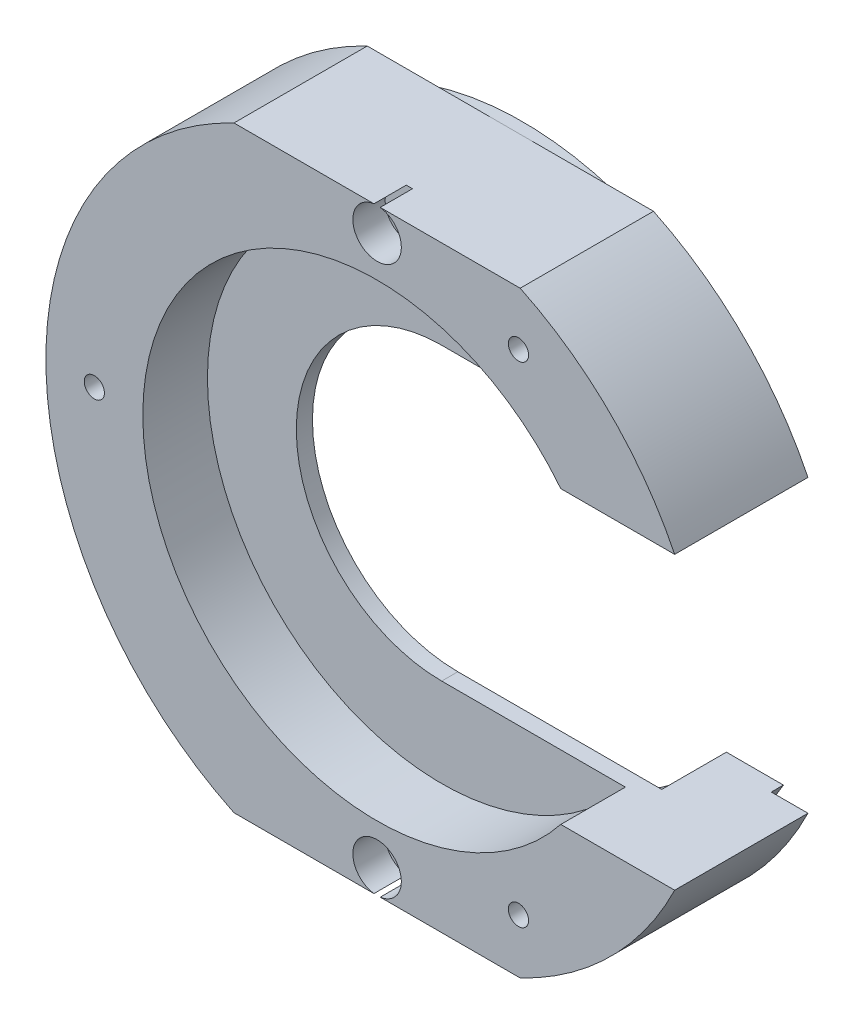
SolidWorks part; units mm, degrees
ref_plane "前视基准面" through (0, 0, 0) normal (0, 0, 1) x (1, 0, 0)
ref_plane "上视基准面" through (0, 0, 0) normal (0, 1, 0) x (1, 0, 0)
ref_plane "右视基准面" through (0, 0, 0) normal (1, 0, 0) x (0, 0, -1)
other "Configuration Table"
sketch "草图1" plane through (0, 0, 0) normal (0, 0, 1) x (1, 0, 0)
  circle A0 centre (0, 0) radius 41
  dimension "D1" = 82
extrude "凸台-拉伸1" add sketch "草图1" along normal blind 16.5
sketch "草图2" plane through (0, 0, 0) normal (0, 0, -1) x (-1, 0, 0)
  circle A0 centre (0, 0) radius 36.975
  dimension "D1" = 73.95
extrude "凸台-拉伸2" add sketch "草图2" along normal blind 1.5
sketch "草图4" plane through (0, 0, -1.5) normal (0, 0, -1) x (-1, 0, 0)
  line L0 (-25, 36.975) -> (25, 36.975) construction
  line L1 (0, 0) -> (11.911, 0) construction
  line L2 (-25, 36.975) -> (25, 36.975)
  line L3 (-25, 36.975) -> (-25, 43.815)
  line L4 (-25, 43.815) -> (25, 43.815)
  line L5 (25, 36.975) -> (25, 43.815)
  line L6 (25, -36.975) -> (25, -43.815)
  line L7 (-25, -43.815) -> (25, -43.815)
  line L8 (-25, -36.975) -> (25, -36.975)
  line L9 (-25, -36.975) -> (-25, -43.815)
  circle A1 centre (0, 0) radius 36.975 construction
  point P4 (0, 36.975)
  dimension "D1" = 6.84
  dimension "D2" = 50
extrude "切除-拉伸1" cut sketch "草图4" against normal through all
sketch "草图5" plane through (0, 0, -1.5) normal (0, 0, -1) x (-1, 0, 0)
  circle A0 centre (0, 0) radius 31
  dimension "D1" = 62
extrude "切除-拉伸3" cut sketch "草图5" against normal blind 8
sketch "草图6" plane through (0, 0, 16.5) normal (0, 0, 1) x (1, 0, 0)
  circle A0 centre (0, 0) radius 29
  dimension "D1" = 58
extrude "切除-拉伸4" cut sketch "草图6" against normal blind 8
sketch "草图7" plane through (0, 0, 8.5) normal (0, 0, 1) x (1, 0, 0)
  line L0 (0, 18) -> (36.8375, 18)
  line L1 (0, -18) -> (36.8375, -18)
  arc A0 (0, 18) -> (0, -18) centre (0, 0) ccw
  arc A1 (17.7158, -36.975) -> (17.7158, 36.975) centre (0, 0) ccw construction
  arc A2 (36.8375, -18) -> (36.8375, 18) centre (0, 0) ccw
  dimension "D1" = 36
extrude "切除-拉伸5" cut sketch "草图7" against normal through all both and the other way through all
sketch "草图8" plane through (0, 0, 16.5) normal (0, 0, 1) x (1, 0, 0)
  line L0 (0, 0) -> (-35, 0) construction
  line L1 (0, 34) -> (0, -34) construction
  circle A0 centre (0, 0) radius 35 construction
  circle A1 centre (0, 0) radius 34 construction
  dimension "D1" = 70
  dimension "D2" = 68
hole_wizard "M3 六角头螺栓的柱形沉头孔3" positions "3D草图3" profile "草图12" counterbore size "M3" standard "GB" end condition through all
sketch3d "3D草图3"
  point P0 (0, 34, 16.5)
  point P3 (0, 34, 16.5)
  point P5 (0, -34, 16.5)
  point P8 (0, -34, 16.5)
sketch "草图12" plane through (0, 34, 16.5) normal (1, 0, 0) x (0, -1, 0)
  line L0 (0, 0) -> (0, 18)
  line L1 (0, 18) -> (1.75, 18)
  line L3 (1.75, 18) -> (1.75, 4)
  line L4 (1.75, 4) -> (3, 4)
  line L5 (3, 4) -> (3, 0)
  line L7 (3, 0) -> (0, 0)
  line L11 (0, -6.35) -> (0, 107.95) construction
  dimension "通孔孔直径" = 3.5
  dimension "通孔孔深度" = 18
  dimension "柱形沉头孔直径" = 6
  dimension "柱形沉头孔深度" = 4
hole_wizard "M3 螺纹孔1" positions "3D草图4" profile "草图13" tap size "M3" standard "GB" end condition through all
sketch3d "3D草图4"
  point P0 (-35, 0, 16.5)
  point P3 (-35, 0, 16.5)
sketch "草图13" plane through (-35, 0, 16.5) normal (1, 0, 0) x (0, -1, 0)
  line L0 (0, 0) -> (0, 18)
  line L1 (0, 18) -> (1.25, 18)
  line L2 (1.25, 18) -> (1.25, 0)
  line L5 (1.25, 0) -> (0, 0)
  line L11 (0, -6.35) -> (0, 107.95) construction
  dimension "通孔螺纹孔钻头直径" = 2.5
  dimension "通孔螺纹孔钻头深度" = 18
cosmetic thread "孔螺纹线2" parameters "D2"=3
pattern_circular "阵列(圆周)1" count 3 over 360 about axis through (0, 0, 0) along (0, 0, 1) of "M3 螺纹孔1"
